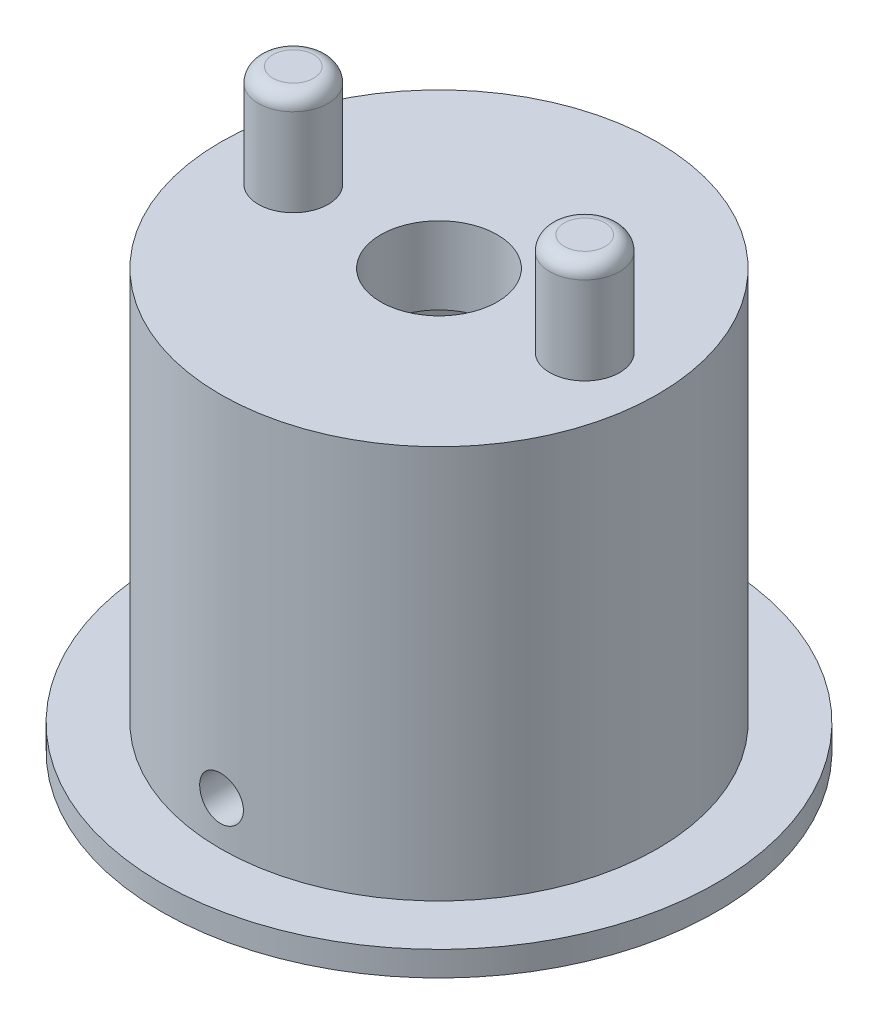
SolidWorks part; units mm, degrees
ref_plane "Front Plane" through (0, 0, 0) normal (0, 0, 1) x (1, 0, 0)
ref_plane "Top Plane" through (0, 0, 0) normal (0, 1, 0) x (1, 0, 0)
ref_plane "Right Plane" through (0, 0, 0) normal (1, 0, 0) x (0, 0, -1)
sketch "Sketch1" plane through (0, 0, 0) normal (0, 1, 0) x (1, 0, 0)
  circle A0 centre (0, 0) radius 15
  dimension "D1" = 30
extrude "Boss-Extrude1" add sketch "Sketch1" along normal blind 27
sketch "Sketch2" plane through (0, 0, 0) normal (0, -1, 0) x (1, 0, 0)
  circle A0 centre (0, 0) radius 19.07
  dimension "D1" = 38.14
extrude "Boss-Extrude2" add sketch "Sketch2" along normal blind 1.7
sketch "Sketch3" plane through (0, -1.7, 0) normal (0, -1, 0) x (1, 0, 0)
  line L1 (-2.8001, 4.85) -> (-5.6003, 0)
  line L2 (-5.6003, 0) -> (-2.8001, -4.85)
  line L3 (-2.8001, -4.85) -> (2.8001, -4.85)
  line L4 (2.8001, -4.85) -> (5.6003, 0)
  line L5 (5.6003, 0) -> (2.8001, 4.85)
  line L6 (2.8001, 4.85) -> (-2.8001, 4.85)
  circle A0 centre (0, 0) radius 4.85 construction
  point P1 (-5.6003, 0)
  dimension "D1" = 9.7
extrude "Cut-Extrude1" cut sketch "Sketch3" against normal blind 23.4
sketch "Sketch4" plane through (0, 21.7, 0) normal (0, -1, 0) x (1, 0, 0)
  circle A0 centre (0, 0) radius 4
  dimension "D1" = 8
extrude "Cut-Extrude2" cut sketch "Sketch4" against normal up to surface (5.3 mm away) up to face at (0, 27, 15)
sketch "Sketch5" plane through (0, 27, 0) normal (0, 1, 0) x (1, 0, 0)
  line L0 (-15, 0) -> (15, 0) construction
  circle A0 centre (0, 0) radius 15 construction
  circle A1 centre (0, 0) radius 15 construction
  circle A2 centre (-10, 0) radius 2.4
  circle A3 centre (10, 0) radius 2.4
  point P11 (-12.4, 0)
  point P12 (12.4, 0)
  dimension "D1" = 4.8
  dimension "D2" = 20
  dimension "D3" = 10
extrude "Boss-Extrude3" add sketch "Sketch5" along normal blind 7
fillet "Fillet1" radius 1 2 edges at (10, 34, 2.4) (-10, 34, 2.4)
sketch "Sketch6" plane through (0, 0, 0) normal (0, 0, 1) x (1, 0, 0)
  line L0 (0, 0) -> (0, 27) construction
  line L1 (15, 27) -> (-15, 27) construction
  circle A0 centre (0, 3) radius 1.5
  dimension "D1" = 3
  dimension "D2" = 24
extrude "Cut-Extrude3" cut sketch "Sketch6" against normal through all and the other way through all
